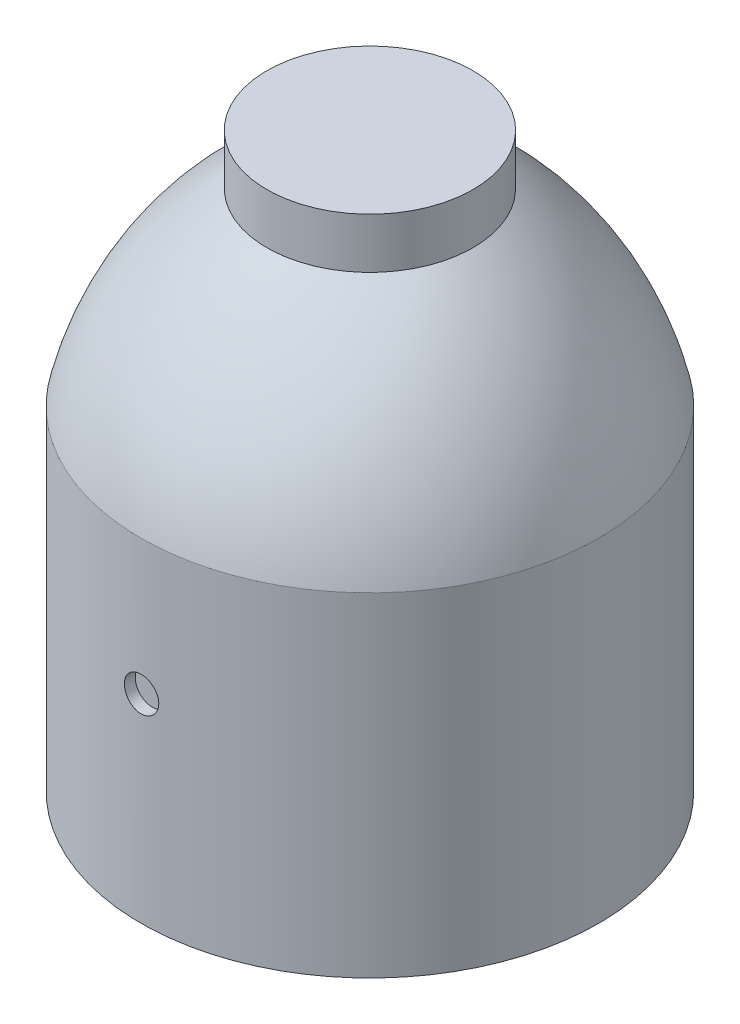
SolidWorks part; units mm, degrees
ref_plane "Front Plane" through (0, 0, 0) normal (0, 0, 1) x (1, 0, 0)
ref_plane "Top Plane" through (0, 0, 0) normal (0, 1, 0) x (1, 0, 0)
ref_plane "Right Plane" through (0, 0, 0) normal (1, 0, 0) x (0, 0, -1)
sketch "Sketch1" plane through (0, 0, 0) normal (0, 0, 1) x (1, 0, 0)
  line L0 (0, 0) -> (0, 50) construction
  line L1 (20, 0) -> (20, 29.1391)
  line L2 (9, 45.5981) -> (9, 50)
  line L3 (9, 50) -> (0, 50)
  line L4 (18, 0) -> (18, 28.9042)
  line L5 (7.8347, 43.9727) -> (0, 43.9727)
  line L6 (20, 0) -> (18, 0)
  line L7 (0, 50) -> (0, 43.9727)
  arc A0 (20, 29.1391) -> (9, 45.5981) centre (-7.3875, 22.7406) ccw
  arc A1 (18, 28.9042) -> (7.8347, 43.9727) centre (-7.3875, 22.7406) ccw
  point P14 (0, 44.0764)
  dimension "D3" = 18
  dimension "D4" = 28.125
  dimension "D1" = 50
  dimension "D2" = 40
  dimension "D5" = 7.3875
  dimension "D6" = 22.7406
  dimension "D7" = 2
revolve "Revolve1" add sketch "Sketch1" angle 360 about L0
ref_plane "Plane1" through (0, 0, 20) normal (0, 0, 1) x (1, 0, 0)
sketch "Sketch2" plane through (0, 0, 20) normal (0, 0, 1) x (1, 0, 0)
  circle A0 centre (0, 17.3474) radius 1.5
  dimension "D1" = 3
  dimension "D2" = 17.3474
extrude "Cut-Extrude1" cut sketch "Sketch2" against normal blind 1
